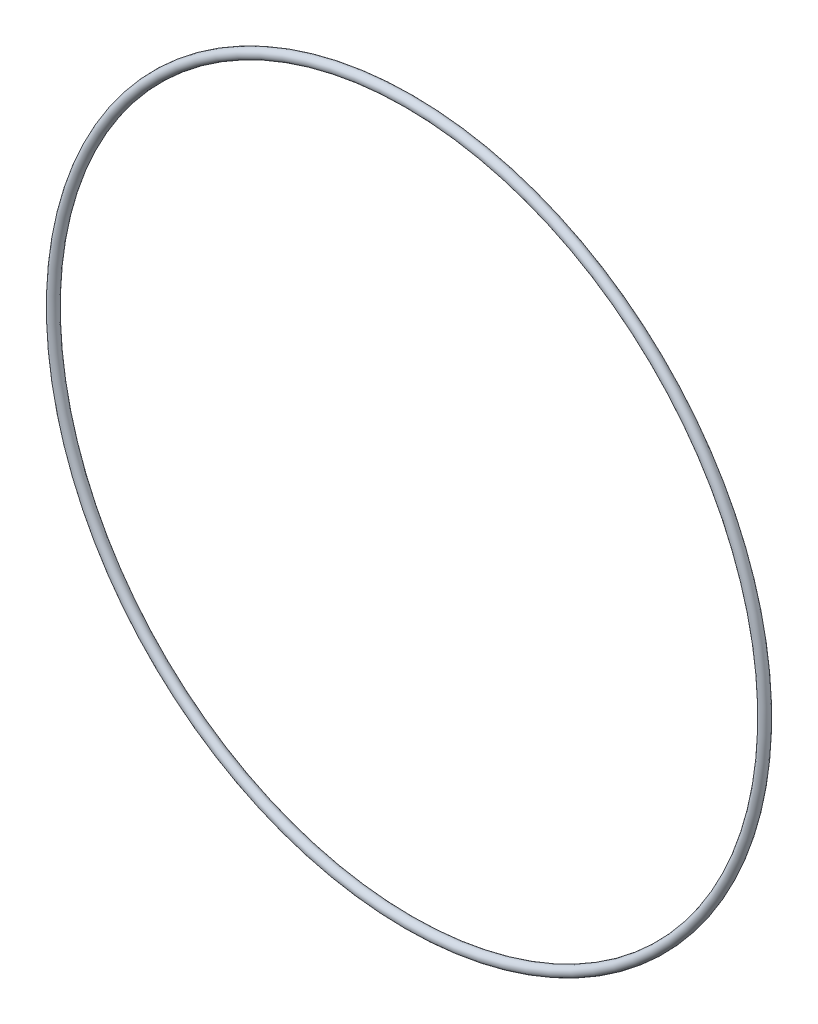
SolidWorks part; units mm, degrees
ref_plane "Front Plane" through (0, 0, 0) normal (0, 0, 1) x (1, 0, 0)
ref_plane "Top Plane" through (0, 0, 0) normal (0, 1, 0) x (1, 0, 0)
ref_plane "Right Plane" through (0, 0, 0) normal (1, 0, 0) x (0, 0, -1)
sketch "Sketch1" plane through (0, 0, 0) normal (1, 0, 0) x (0, 0, -1)
  line L0 (0, -63.3603) -> (0, 63.3603) construction
  circle A0 centre (0, -64.2493) radius 0.889 construction
  circle A1 centre (0, 64.2493) radius 0.889 construction
  point P3 (-0.889, -63.3603)
  point P4 (0, 0)
  point P7 (0, -65.1383)
  point P8 (-0.889, -64.2493)
  point P9 (0.889, -64.2493)
  point P12 (0, 65.1383)
  dimension "ID" = 126.7206
  dimension "OD" = 130.2766
  dimension "Width" = 1.778
sketch "Sketch2" plane through (0, 0, 0) normal (1, 0, 0) x (0, 0, -1)
  line L0 (-63.3603, 0) -> (63.3603, 0) construction
  line L1 (0, -63.3603) -> (0, 63.3603) construction
  circle A0 centre (0, 64.2493) radius 0.889 construction
  circle A1 centre (0, 64.2493) radius 0.889
  point P7 (0, 0)
revolve "Revolve1" add sketch "Sketch2" angle 360 about L0
sketch "Drawing Reference 1" plane through (0, 0, 0) normal (0, 0, 1) x (1, 0, 0)
  circle A0 centre (0, 0) radius 65.1383
  circle A1 centre (0, 0) radius 63.3603
